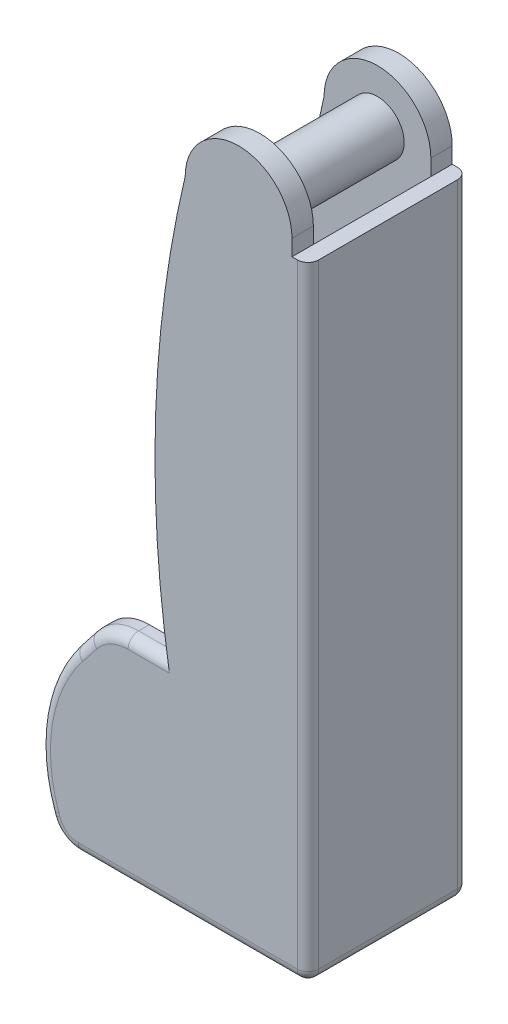
SolidWorks part; units mm, degrees
ref_plane "Front Plane" through (0, 0, 0) normal (0, 0, 1) x (1, 0, 0)
ref_plane "Top Plane" through (0, 0, 0) normal (0, 1, 0) x (1, 0, 0)
ref_plane "Right Plane" through (0, 0, 0) normal (1, 0, 0) x (0, 0, -1)
sketch "Sketch1" plane through (0, 0, 0) normal (0, 0, 1) x (1, 0, 0)
  line L0 (0, -55) -> (0, 55) construction
  line L1 (5, 41.701) -> (6.5, 41.701)
  line L2 (6.5, 41.701) -> (6.5, -18.299)
  line L3 (6.5, -18.299) -> (-17, -18.299)
  line L7 (-6.6313, 1.701) -> (-12.6313, 1.701)
  line L8 (-12.6313, 1.701) -> (-20.5, -8.299)
  line L9 (-20.5, -8.299) -> (-17, -18.299)
  arc A0 (5, 41.701) -> (-5, 41.701) centre (0, 41.701) ccw
  arc A1 (-6.6313, 1.701) -> (-5, 41.701) centre (97.1732, 17.5009) cw
  dimension "D1" = 10
  dimension "D3" = 105
  dimension "D2" = 1.5
  dimension "D4" = 27
  dimension "D5" = 60
  dimension "D6" = 6
  dimension "D7" = 10
  dimension "D8" = 3.5
  dimension "D9" = 10
extrude "Boss-Extrude1" add sketch "Sketch1" along normal mid plane 15
sketch "Sketch3" plane through (0, 0, 0) normal (1, 0, 0) x (0, 0, -1)
  line L0 (7.5, 46.701) -> (-7.5, 46.701) construction
  line L1 (-5.5, 46.701) -> (5.5, 46.701)
  line L2 (-5.5, 46.701) -> (-5.5, -18.299)
  line L3 (-5.5, -18.299) -> (5.5, -18.299)
  line L4 (5.5, 46.701) -> (5.5, -18.299)
  line L5 (-7.5, -18.299) -> (7.5, -18.299) construction
  line L6 (7.5, -18.299) -> (7.5, 41.701) construction
  line L7 (-7.5, -18.299) -> (-7.5, 41.701) construction
  dimension "D1" = 2
  dimension "D2" = 2
extrude "Cut-Extrude1" cut sketch "Sketch3" against normal blind 25 and the other way blind 5
sketch "Sketch5" plane through (0, 0, -5.5) normal (0, 0, 1) x (1, 0, 0)
  circle A0 centre (0, 41.701) radius 2.5
  dimension "D1" = 5
extrude "Boss-Extrude3" add sketch "Sketch5" along normal blind 11
sketch "Sketch6" plane through (0, 0, 7.5) normal (0, 0, 1) x (1, 0, 0)
  line L0 (0, -8.25) -> (0, 8.25) construction
  line L1 (-17, -18.299) -> (6.5, -18.299) construction
  circle A0 centre (0, -13.299) radius 2.5
  dimension "D1" = 5
  dimension "D2" = 5
extrude "Boss-Extrude4" add sketch "Sketch6" against normal up to surface (13 mm away) up to face at (-7.6695, 6.7122, -5.5)
fillet "Fillet1" radius 1 2 edges at (6.5, 11.701, -7.5) (6.5, 11.701, 7.5)
fillet "Fillet2" radius 4.7 2 edges at (-12.6313, 1.701, 6.5) (-12.6313, 1.701, -6.5)
fillet "Fillet3" radius 15.1 2 edges at (-20.5, -8.299, 6.5) (-20.5, -8.299, -6.5)
fillet "Fillet4" radius 2.8 2 edges at (-17, -18.299, 6.5) (-17, -18.299, -6.5)
fillet "Fillet7" radius 1 17 edges at (-8.4901, 1.701, 7.5) (-12.402, 1.2288, 7.5) (-14.7105, -0.9415, 7.5) (-18.4066, -8.6476, 7.5) (-17.7101, -16.2701, 7.5) (-16.6336, -17.7827, 7.5) (-4.7567, -18.299, 7.5) (6.2071, -18.299, 7.2071) (-8.4901, 1.701, -7.5) (-12.402, 1.2288, -7.5) (-14.7105, -0.9415, -7.5) (-18.4066, -8.6476, -7.5) (-17.7101, -16.2701, -7.5) (-16.6336, -17.7827, -7.5) (-4.7567, -18.299, -7.5) (6.2071, -18.299, -7.2071) (6.5, -18.299, 0)
sketch "Sketch7" plane through (0, 41.701, 0) normal (0, 1, 0) x (1, 0, 0)
  line L6 (6.5, -6.5) -> (6.5, 6.5)
  line L7 (5.5, 7.5) -> (5, 7.5)
  line L8 (5, 7.5) -> (5, 5.5)
  line L9 (5, 5.5) -> (5, -5.5)
  line L10 (5, -5.5) -> (5, -7.5)
  line L11 (5, -7.5) -> (5.5, -7.5)
  line L12 (6.5, -6.5) -> (6.5, 6.5)
  line L13 (5.5, 7.5) -> (5, 7.5)
  line L14 (5, 7.5) -> (5, 5.5)
  line L15 (5, 5.5) -> (5, -5.5)
  line L16 (5, -5.5) -> (5, -7.5)
  line L17 (5, -7.5) -> (5.5, -7.5)
  arc A2 (6.5, 6.5) -> (5.5, 7.5) centre (5.5, 6.5) ccw
  arc A3 (5.5, -7.5) -> (6.5, -6.5) centre (5.5, -6.5) ccw
  arc A4 (6.5, 6.5) -> (5.5, 7.5) centre (5.5, 6.5) ccw
  arc A5 (5.5, -7.5) -> (6.5, -6.5) centre (5.5, -6.5) ccw
  dimension "D1" = 0
extrude "Cut-Extrude2" cut sketch "Sketch7" against normal blind 1.5
